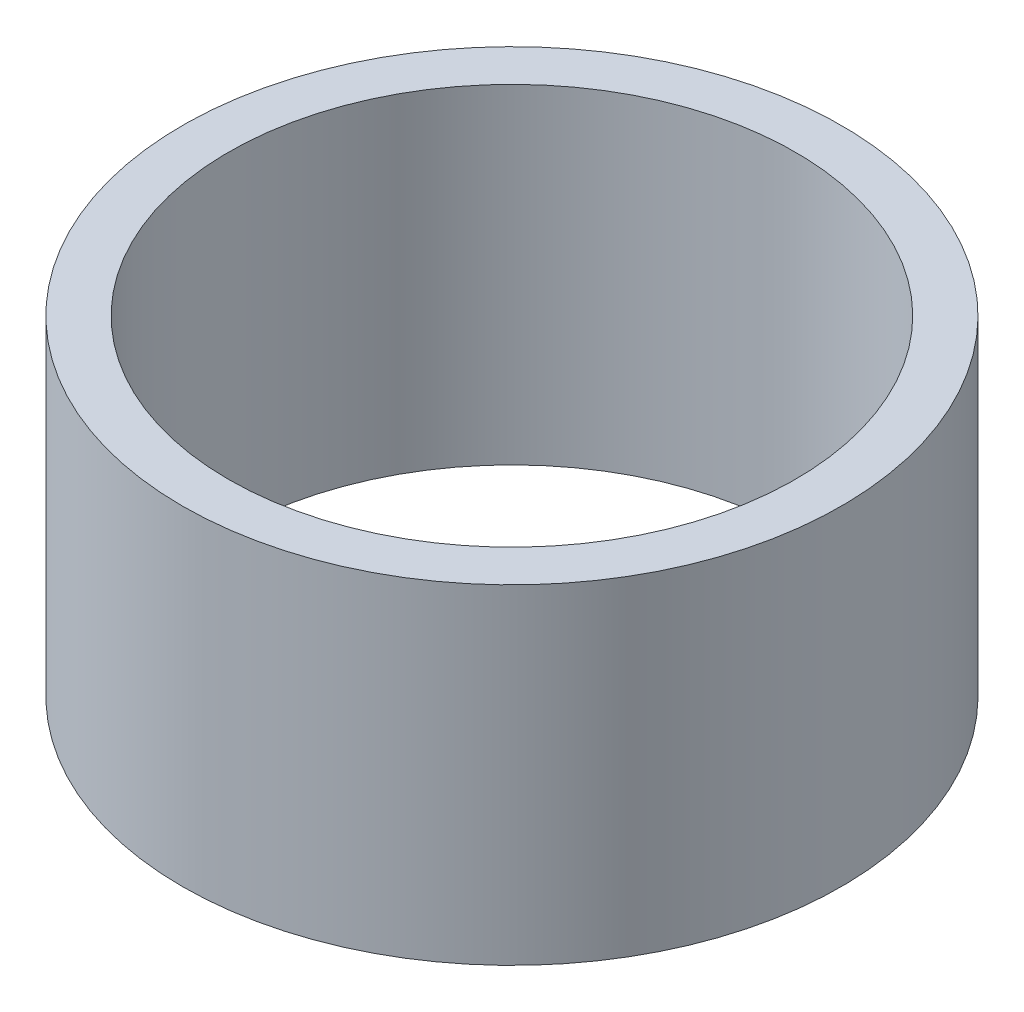
SolidWorks part; units mm, degrees
ref_plane "Front Plane" through (0, 0, 0) normal (0, 0, 1) x (1, 0, 0)
ref_plane "Top Plane" through (0, 0, 0) normal (0, 1, 0) x (1, 0, 0)
ref_plane "Right Plane" through (0, 0, 0) normal (1, 0, 0) x (0, 0, -1)
sketch "Sketch1" plane through (0, 0, 0) normal (0, 1, 0) x (1, 0, 0)
  circle A0 centre (0, 0) radius 4.3
  circle A1 centre (0, 0) radius 5
  dimension "D1" = 10
  dimension "D2" = 8.6
extrude "Boss-Extrude1" add sketch "Sketch1" along normal blind 5
